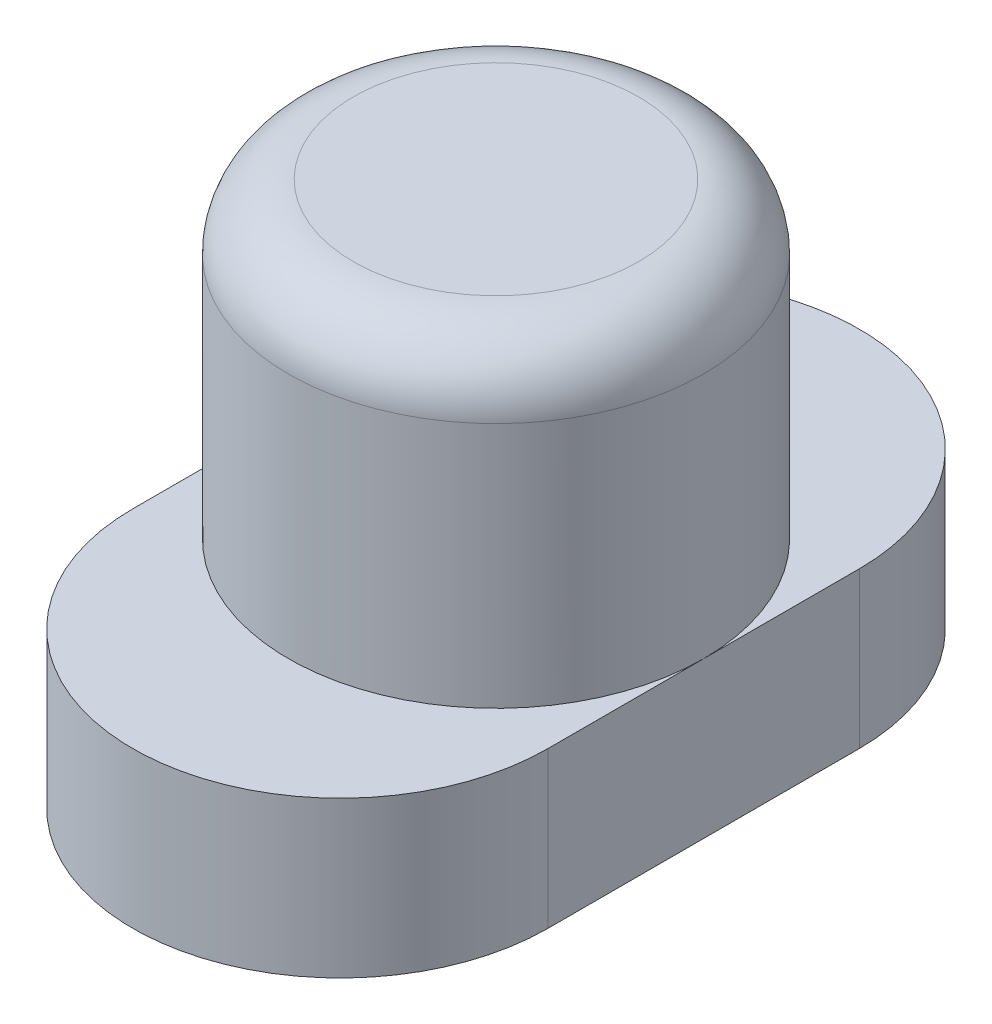
SolidWorks part; units mm, degrees
ref_plane "Front Plane" through (0, 0, 0) normal (0, 0, 1) x (1, 0, 0)
ref_plane "Top Plane" through (0, 0, 0) normal (0, 1, 0) x (1, 0, 0)
ref_plane "Right Plane" through (0, 0, 0) normal (1, 0, 0) x (0, 0, -1)
sketch "Sketch1" plane through (0, 0, 0) normal (0, 0, 1) x (1, 0, 0)
  line L1 (0, 9) -> (4, 9)
  line L2 (4, 9) -> (4, 3)
  line L3 (4, 3) -> (7, 3)
  line L4 (7, 3) -> (7, 0)
  line L6 (0, 9) -> (0, 6.9292) construction
  line L7 (0, 9) -> (0, 0)
  line L10 (0, 0) -> (7, 0)
  dimension "D1" = 4
  dimension "D2" = 3
  dimension "D3" = 6
  dimension "D4" = 3
revolve "Revolve1" add sketch "Sketch1" angle 360 about L6
sketch "Sketch2" plane through (0, 0, 0) normal (0, -1, 0) x (1, 0, 0)
  line L1 (-1.75, -1.25) -> (1.75, -1.25)
  line L2 (-1.75, -1.25) -> (-1.75, 1.25)
  line L3 (-1.75, 1.25) -> (1.75, 1.25)
  line L4 (1.75, -1.25) -> (1.75, 1.25)
  line L5 (-1.75, -1.25) -> (1.75, 1.25) construction
  line L6 (-1.75, 1.25) -> (1.75, -1.25) construction
  point P0 (0, 0)
  dimension "D1" = 3.5
  dimension "D2" = 2.5
extrude "Cut-Extrude1" cut sketch "Sketch2" against normal blind 3.5 contours L3 L4 L1 L2
fillet "Fillet1" radius 1.25 1 edges at (-4, 9, 0)
sketch "Sketch3" plane through (0, 0, 0) normal (0, 1, 0) x (1, 0, 0)
  line L0 (0, -3) -> (0, 3) construction
  line L1 (-4, -3) -> (-4, 3)
  line L2 (4, -3) -> (4, 3)
  line L3 (0, 3) -> (0, 7) construction
  line L4 (-14, -3) -> (-14, 3)
  line L5 (14, -3) -> (14, 3)
  arc A1 (-4, -3) -> (4, -3) centre (0, -3) ccw
  arc A2 (4, 3) -> (-4, 3) centre (0, 3) ccw
  circle A3 centre (0, 0) radius 7 construction
  circle A4 centre (0, 0) radius 4 construction
  arc A5 (14, 3) -> (-14, 3) centre (0, 3) ccw
  arc A6 (-14, -3) -> (14, -3) centre (0, -3) ccw
  point P5 (0, 0)
  dimension "D1" = 10
extrude "Cut-Extrude2" cut sketch "Sketch3" along normal through all
